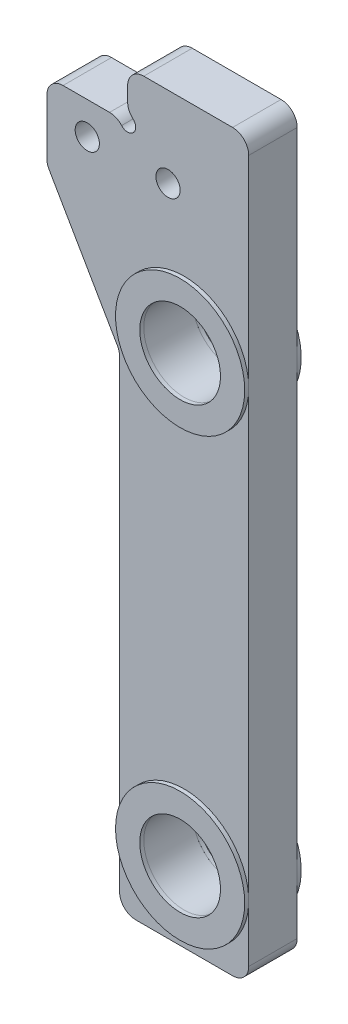
SolidWorks part; units mm, degrees
material "Thornel Mat VMA"
ref_plane "前视基准面" through (0, 0, 0) normal (0, 0, 1) x (1, 0, 0)
ref_plane "上视基准面" through (0, 0, 0) normal (0, 1, 0) x (1, 0, 0)
ref_plane "右视基准面" through (0, 0, 0) normal (1, 0, 0) x (0, 0, -1)
other "Configuration Table"
sketch "草图1" plane through (0, 0, 0) normal (0, 0, 1) x (1, 0, 0)
  line L0 (0, 0) -> (0, -55) construction
  line L1 (8, 20.95) -> (8, -64.05)
  line L2 (8, -64.05) -> (-12, -64.05)
  line L3 (-12, -64.05) -> (-17, -35.6936)
  line L5 (-17, -35.6936) -> (-17, 20.95)
  line L6 (-17, 20.95) -> (8, 20.95)
  line L7 (-2, 16.95) -> (-12, 16.95) construction
  circle A0 centre (0, 0) radius 6
  circle A1 centre (0, -55) radius 6
  circle A2 centre (-2, 16.95) radius 1.5
  circle A3 centre (-12, 16.95) radius 1.5
  dimension "D1" = 12
  dimension "D3" = 10
  dimension "D4" = 3
  dimension "D8" = 20.95
  dimension "D9" = 8
  dimension "D2" = 55
  dimension "D5" = 10
  dimension "D6" = 4
  dimension "D7" = 85
  dimension "D10" = 20
  dimension "D11" = 100
  dimension "D12" = 25
extrude "凸台-拉伸1" add sketch "草图1" along normal blind 6
sketch "草图2" plane through (0, 0, 6) normal (0, 0, 1) x (1, 0, 0)
  circle A0 centre (0, 0) radius 5
  circle A1 centre (0, -55) radius 5
  circle A2 centre (0, -55) radius 6 construction
  circle A3 centre (0, 0) radius 6 construction
  circle A4 centre (0, -55) radius 6
  circle A5 centre (0, 0) radius 6
  dimension "D1" = 10
extrude "凸台-拉伸2" add sketch "草图2" against normal blind 6 separate body
sketch "草图3" plane through (0, 0, 6) normal (0, 0, 1) x (1, 0, 0)
  circle A0 centre (0, 0) radius 8
  circle A1 centre (0, -55) radius 8
  circle A2 centre (0, 0) radius 5 construction
  circle A3 centre (0, -55) radius 5 construction
  circle A4 centre (0, 0) radius 5
  circle A5 centre (0, -55) radius 5
  dimension "D1" = 16
extrude "凸台-拉伸3" add sketch "草图3" along normal blind 0.5 separate body
sketch "草图4" plane through (0, 0, 0) normal (0, 0, -1) x (-1, 0, 0)
  circle A0 centre (0, -55) radius 8 construction
  circle A1 centre (0, -55) radius 5
  circle A2 centre (0, -55) radius 5
  circle A3 centre (0, 0) radius 5
  circle A4 centre (0, 0) radius 5
  circle A5 centre (0, 0) radius 8 construction
  circle A6 centre (0, -55) radius 8
  circle A7 centre (0, 0) radius 8
  dimension "D1" = 0
  dimension "D2" = 0
extrude "凸台-拉伸4" add sketch "草图4" along normal blind 0.5 separate body
sketch "草图5" plane through (0, 0, 0) normal (0, 0, -1) x (-1, 0, 0)
  line L0 (-8, -64.05) -> (-8, 20.95) construction
  line L1 (-8, 20.95) -> (7, 20.95)
  line L2 (-8, 20.95) -> (-8, 26.95)
  line L3 (-8, 26.95) -> (7, 26.95)
  line L4 (7, 20.95) -> (7, 26.95)
  dimension "D1" = 15
  dimension "D2" = 6
extrude "凸台-拉伸5" add sketch "草图5" against normal blind 6
sketch "草图6" plane through (0, 0, 0) normal (0, 0, -1) x (-1, 0, 0)
  circle A0 centre (7, 20.95) radius 1
  dimension "D1" = 2
extrude "切除-拉伸1" cut sketch "草图6" against normal blind 6
sketch "草图9" plane through (0, 0, 6) normal (0, 0, 1) x (1, 0, 0)
  line L0 (-8, -64.05) -> (-8, -4.05)
  line L1 (-12, -64.05) -> (8, -64.05) construction
  line L2 (-8, -4.05) -> (-17, 11.5385)
  line L3 (-17, 20.95) -> (-17, -35.6936) construction
  line L11 (-7, 26.95) -> (-7, 21.95)
  line L12 (-8, 20.95) -> (-17, 20.95)
  line L13 (-17, 20.95) -> (-17, -35.6936)
  line L14 (-17, -35.6936) -> (-12, -64.05)
  line L15 (-12, -64.05) -> (8, -64.05)
  line L16 (8, -64.05) -> (8, 26.95)
  line L17 (8, 26.95) -> (-7, 26.95)
  line L18 (-7, 26.95) -> (-7, 21.95)
  line L19 (-8, 20.95) -> (-17, 20.95)
  line L20 (-17, 20.95) -> (-17, -35.6936)
  line L21 (-17, -35.6936) -> (-12, -64.05)
  line L22 (-12, -64.05) -> (8, -64.05)
  line L23 (8, -64.05) -> (8, 26.95)
  line L24 (8, 26.95) -> (-7, 26.95)
  arc A1 (-8, 20.95) -> (-7, 21.95) centre (-7, 20.95) ccw
  arc A2 (-8, 20.95) -> (-7, 21.95) centre (-7, 20.95) ccw
  line M14 (-17, 20.95) -> (-17, -35.6936)
  line M15 (-17, -35.6936) -> (-12, -64.05)
  line M16 (-12, -64.05) -> (8, -64.05)
  dimension "D2" = 16
  dimension "D3" = 60
  dimension "D4" = 30
  dimension "D1" = 0
extrude "切除-拉伸4" cut sketch "草图9" against normal blind 6 contours L0 L2 M14 M15 M16
fillet "圆角5" radius 2 9 edges at (-17, 11.5385, 3) (-8, 20.95, 3) (-7, 21.95, 3) (-7, 26.95, 3) (8, 26.95, 3) (8, -64.05, 3) (-8, -64.05, 3) (-8, -4.05, 3) (-17, 20.95, 3)
